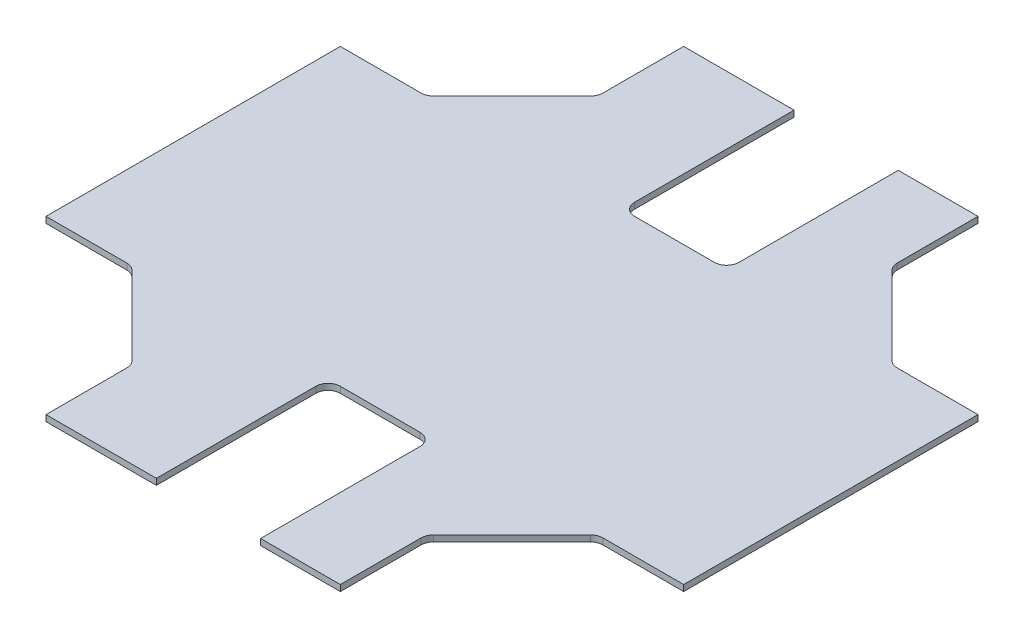
SolidWorks part; units mm, degrees
material "ABS PC"
ref_plane "Front Plane" through (0, 0, 0) normal (0, 0, 1) x (1, 0, 0)
ref_plane "Top Plane" through (0, 0, 0) normal (0, 1, 0) x (1, 0, 0)
ref_plane "Right Plane" through (0, 0, 0) normal (1, 0, 0) x (0, 0, -1)
sketch "Sketch1" plane through (0, 0, 0) normal (0, 1, 0) x (1, 0, 0)
  line L0 (-330.2, -152.4) -> (-241.3, -152.4)
  line L1 (-330.2, 330.2) -> (330.2, 330.2)
  line L2 (-330.2, 330.2) -> (-330.2, -330.2)
  line L3 (-330.2, -330.2) -> (330.2, -330.2)
  line L4 (330.2, 330.2) -> (330.2, -330.2)
  line L5 (-330.2, 330.2) -> (330.2, -330.2) construction
  line L6 (-330.2, -330.2) -> (330.2, 330.2) construction
  line L7 (-241.3, -152.4) -> (-152.4, -241.3)
  line L8 (-152.4, -241.3) -> (-152.4, -330.2)
  line L9 (-152.4, 330.2) -> (-152.4, 241.3)
  line L10 (-152.4, 241.3) -> (-241.3, 152.4)
  line L11 (-241.3, 152.4) -> (-330.2, 152.4)
  line L12 (330.2, 152.4) -> (241.3, 152.4)
  line L13 (241.3, 152.4) -> (152.4, 241.3)
  line L14 (152.4, 241.3) -> (152.4, 330.2)
  line L15 (152.4, -330.2) -> (152.4, -241.3)
  line L16 (152.4, -241.3) -> (241.3, -152.4)
  line L17 (241.3, -152.4) -> (330.2, -152.4)
  point P0 (0, 0)
  point P25 (0, 0)
  dimension "D1" = 660.4
  dimension "D2" = 660.4
  dimension "D3" = 88.9
  dimension "D4" = 177.8
  dimension "D5" = 177.8
  dimension "D6" = 88.9
  dimension "D7" = 4
extrude "Boss-Extrude1" add sketch "Sketch1" along normal blind 6.35 contours L16 L17 L4 L12 L13 L14 L1 L9 L10 L11 L2 L0 L7 L8 L3 L15
sketch "Sketch3" plane through (0, 6.35, 0) normal (0, 1, 0) x (1, 0, 0)
  line L0 (330.2, 0) -> (-330.2, 0) construction
  line L1 (330.2, 152.4) -> (330.2, -152.4) construction
  line L2 (-330.2, 152.4) -> (-330.2, -152.4) construction
  line L3 (-152.4, 330.2) -> (152.4, 330.2) construction
  line L4 (69.85, 330.2) -> (-38.1, 330.2)
  line L5 (69.85, 330.2) -> (69.85, 165.1)
  line L6 (57.15, 152.4) -> (-25.4, 152.4)
  line L7 (-38.1, 330.2) -> (-38.1, 165.1)
  line L8 (152.4, 241.3) -> (152.4, 330.2) construction
  line L9 (-152.4, 330.2) -> (-152.4, 241.3) construction
  line L10 (69.85, -330.2) -> (-38.1, -330.2)
  line L11 (-38.1, -330.2) -> (-38.1, -165.1)
  line L12 (57.15, -152.4) -> (-25.4, -152.4)
  line L13 (69.85, -330.2) -> (69.85, -165.1)
  arc A0 (-25.4, 152.4) -> (-38.1, 165.1) centre (-25.4, 165.1) cw
  arc A1 (69.85, 165.1) -> (57.15, 152.4) centre (57.15, 165.1) cw
  arc A2 (-25.4, -152.4) -> (-38.1, -165.1) centre (-25.4, -165.1) ccw
  arc A3 (69.85, -165.1) -> (57.15, -152.4) centre (57.15, -165.1) ccw
  point P20 (69.85, 152.4)
  dimension "D4" = 12.7
  dimension "D1" = 177.8
  dimension "D2" = 82.55
  dimension "D3" = 114.3
extrude "Cut-Extrude2" cut sketch "Sketch3" against normal through all
fillet "Fillet1" radius 12.7 8 edges at (152.4, 3.175, 241.3) (241.3, 3.175, 152.4) (-152.4, 3.175, 241.3) (-241.3, 3.175, 152.4) (-241.3, 3.175, -152.4) (-152.4, 3.175, -241.3) (152.4, 3.175, -241.3) (241.3, 3.175, -152.4)
